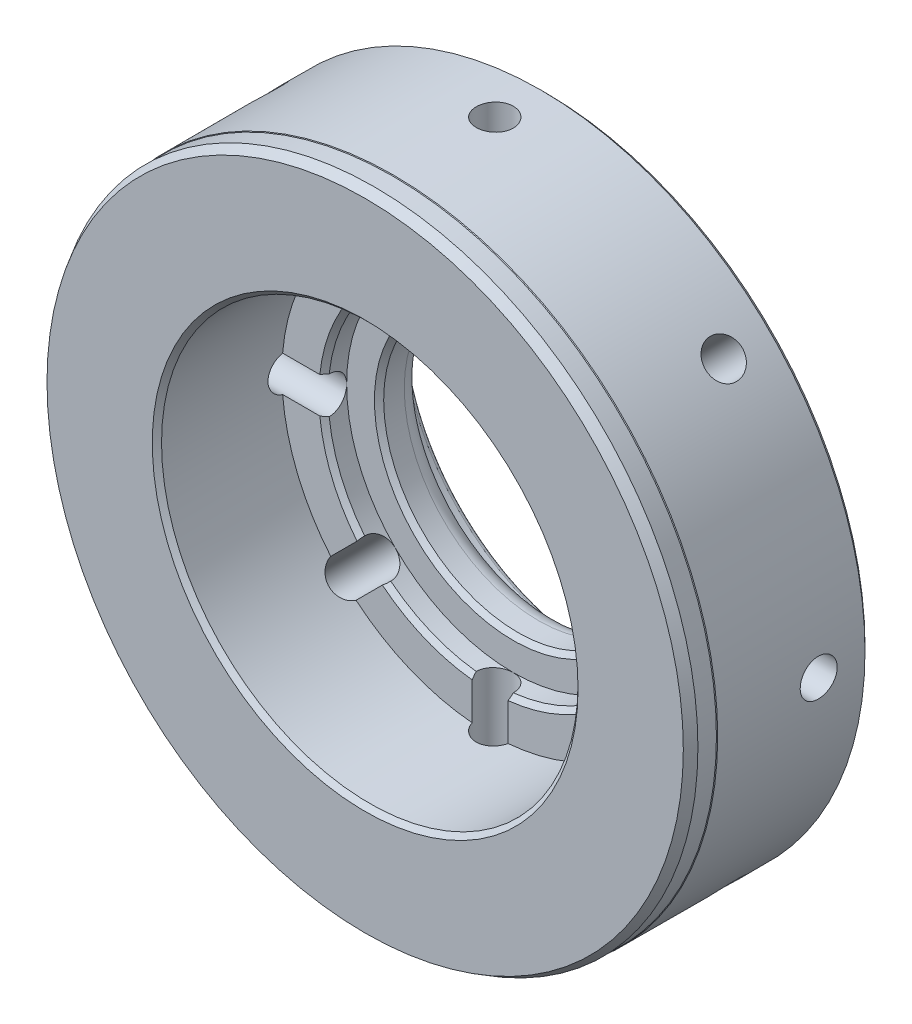
SolidWorks part; units mm, degrees
material "4140 H/T"
ref_plane "Front" through (0, 0, 0) normal (0, 0, 1) x (1, 0, 0)
ref_plane "Top" through (0, 0, 0) normal (0, 1, 0) x (1, 0, 0)
ref_plane "Right" through (0, 0, 0) normal (1, 0, 0) x (0, 0, -1)
sketch "Sketch1" plane through (0, 0, 0) normal (1, 0, 0) x (0, 0, -1)
  line L0 (0, 0) -> (25.5, 0) construction
  line L1 (1, 34.95) -> (3, 34.95)
  line L2 (0, 34.3726) -> (0, 23)
  line L3 (25.5, 26) -> (25.5, 21.5)
  line L4 (19.5, 34.5) -> (19.5, 26.5)
  line L5 (19.5, 26.5) -> (25, 26.5)
  line L7 (0, 26.5) -> (25.5, 26.5) construction
  line L8 (19.5, 35) -> (19.5, 0) construction
  line L9 (25.5, 35) -> (25.5, 0) construction
  line L10 (0.5, 22.5) -> (13.5, 22.5)
  line L13 (0, 34.95) -> (25.5, 34.95) construction
  line L17 (3.0866, 35) -> (19, 35)
  line L18 (0, 35) -> (0, 0) construction
  line L19 (14, 18) -> (16, 18)
  line L20 (13.5, 22.5) -> (13.5, 18.5)
  line L21 (16, 18) -> (16, 15)
  line L22 (0, 18) -> (25.5, 18) construction
  line L23 (13.5, 34.95) -> (13.5, 0) construction
  line L24 (0, 22.5) -> (25.5, 22.5) construction
  line L25 (16.5, 14.5) -> (18.7237, 14.5)
  line L26 (22, 21) -> (25, 21)
  line L27 (0, 14.5) -> (25.5, 14.5) construction
  line L28 (16, 34.95) -> (16, 0) construction
  line L29 (0, 34.95) -> (0, 0) construction
  line L30 (0, 21) -> (25.5, 21) construction
  line L31 (22, 21) -> (20.6555, 15.9824)
  line L32 (0, 34.3726) -> (1, 34.95)
  line L33 (3, 34.95) -> (3.0866, 35)
  line L34 (0, 23) -> (0.5, 22.5)
  line L36 (19, 35) -> (19.5, 34.5)
  line L37 (25, 26.5) -> (25.5, 26)
  line L39 (16, 15) -> (16.5, 14.5)
  line L40 (13.5, 18.5) -> (14, 18)
  arc A0 (20.6555, 15.9824) -> (18.7237, 14.5) centre (18.7237, 16.5) cw
  arc A1 (25, 21) -> (25.5, 21.5) centre (25, 21.5) ccw
  point P10 (0, 33.5)
  point P11 (25.5, 33.5)
  point P12 (4, 35)
  point P13 (4, 0)
  point P14 (6.6, 35)
  point P15 (6.6, 0)
  point P27 (13.5, 18)
  point P33 (16, 14.5)
  point P38 (22, 26.5)
  point P39 (22, 0)
  dimension "D17" = 2
  dimension "D21" = 0.5
  dimension "D1" = 25.5
  dimension "D2" = 35
  dimension "D3" = 34.95
  dimension "D4" = 3
  dimension "D5" = 0.5
  dimension "D7" = 26.5
  dimension "D8" = 6
  dimension "D9" = 13.5
  dimension "D10" = 15
  dimension "D11" = 21
  dimension "D12" = 14.5
  dimension "D13" = 18
  dimension "D14" = 22.5
  dimension "D15" = 16
  dimension "D16" = 3.5
  dimension "D18" = 1
  dimension "D19" = 30
  dimension "D20" = 30
  dimension "D23" = 45
  dimension "D25" = 0.5
  dimension "D27" = 45
  dimension "D28" = 45
  dimension "D29" = 0.5
  dimension "D31" = 45
  dimension "D32" = 0.5
  dimension "D33" = 45
  dimension "D35" = 0.5
revolve "Revolve1" add sketch "Sketch1" angle 360 about L0
ref_plane "Plane1" through (0, 35, 0) normal (0, 1, 0) x (1, 0, 0)
hole_wizard "Ø4.0 (4) Diameter Hole1" positions "Sketch3" profile "Sketch2" hole size "Ø4.0" standard "ISO"
sketch "Sketch3" plane through (0, 35, 0) normal (0, 1, 0) x (1, 0, 0)
  line L0 (26, 25.5) -> (-26, 25.5) construction
  point P0 (0, 14)
  dimension "D1" = 11.5
sketch "Sketch2" plane through (0, 35, -14) normal (1, 0, 0) x (0, 0, 1)
  line L0 (0, 0) -> (0, 26.2017)
  line L1 (0, 26.2017) -> (2, 25)
  line L2 (2, 25) -> (2, 0)
  line L5 (2, 0) -> (0, 0)
  line L10 (0, 26.2017) -> (-2, 25) construction
  line L11 (0, -6.35) -> (0, 107.95) construction
  dimension "Hole Dia." = 4
  dimension "Hole Depth" = 25
  dimension "Drill Angle" = 118
pattern_circular "CirPattern1" count 8 over 360 of "Ø4.0 (4) Diameter Hole1"
